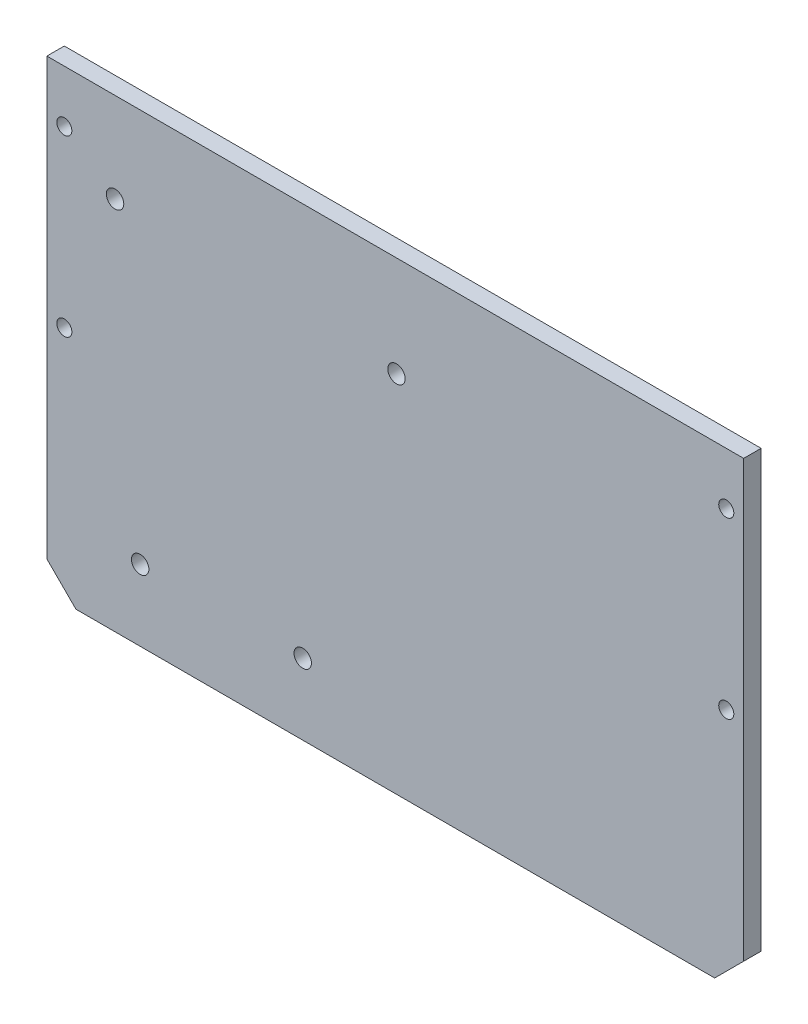
SolidWorks part; units mm, degrees
ref_plane "前视基准面" through (0, 0, 0) normal (0, 0, 1) x (1, 0, 0)
ref_plane "上视基准面" through (0, 0, 0) normal (0, 1, 0) x (1, 0, 0)
ref_plane "右视基准面" through (0, 0, 0) normal (1, 0, 0) x (0, 0, -1)
sketch "草图1" plane through (0, 0, 0) normal (0, 0, 1) x (1, 0, 0)
  line L1 (-60, 40) -> (60, 40)
  line L2 (-60, 40) -> (-60, -40)
  line L3 (-60, -40) -> (60, -40)
  line L4 (60, 40) -> (60, -40)
  line L5 (-60, 40) -> (60, -40) construction
  line L6 (-60, -40) -> (60, 40) construction
  point P0 (0, 0)
  dimension "D1" = 120
  dimension "D2" = 80
extrude "凸台-拉伸1" add sketch "草图1" along normal blind 3
sketch "草图2" plane through (0, 0, 3) normal (0, 0, 1) x (1, 0, 0)
  line L0 (0, 40) -> (0, -40) construction
  line L1 (60, 40) -> (-60, 40) construction
  line L2 (-60, -40) -> (60, -40) construction
  line L3 (-60, 40) -> (-60, -40) construction
  line L4 (-57, 31) -> (-57, 1) construction
  circle A0 centre (-57, 31) radius 1.3
  circle A1 centre (-57, 1) radius 1.3
  circle A2 centre (57, 31) radius 1.3
  circle A3 centre (57, 1) radius 1.3
  dimension "D1" = 3
  dimension "D3" = 30
extrude "切除-拉伸1" cut sketch "草图2" against normal through all
sketch "草图3" plane through (0, 0, 3) normal (0, 0, 1) x (1, 0, 0)
  line L0 (-43.9374, -27.7718) -> (-15.9374, -27.7718) construction
  circle A0 centre (-43.9374, -27.7718) radius 1.5
  circle A1 centre (-15.9374, -27.7718) radius 1.5
  circle A2 centre (-48.2589, 24.5501) radius 1.5
  circle A3 centre (0.2062, 22.7097) radius 1.5
  dimension "D1" = 3
  dimension "D2" = 3
  dimension "D3" = 3
  dimension "D4" = 3
  dimension "D5" = 52.5
  dimension "D6" = 28
  dimension "D7" = 48.5
  dimension "D8" = 53
  dimension "D9" = 61.5
extrude "切除-拉伸2" cut sketch "草图3" against normal through all
chamfer "倒角1" distance 5 angle 45 2 edges at (60, -40, 1.5) (-60, -40, 1.5)
